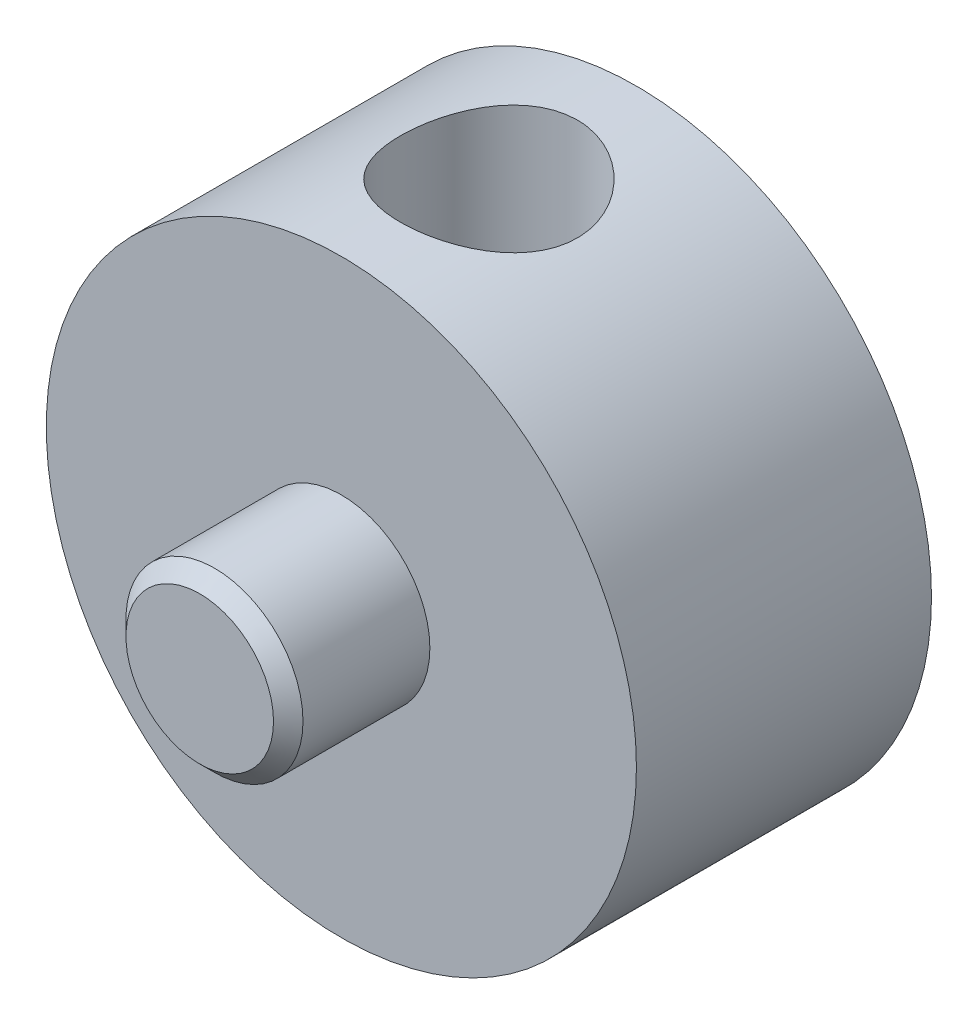
SolidWorks part; units mm, degrees
ref_plane "Piano frontale" through (0, 0, 0) normal (0, 0, 1) x (1, 0, 0)
ref_plane "Piano superiore" through (0, 0, 0) normal (0, 1, 0) x (1, 0, 0)
ref_plane "Piano destro" through (0, 0, 0) normal (1, 0, 0) x (0, 0, -1)
sketch "Schizzo1" plane through (0, 0, 0) normal (0, 0, 1) x (1, 0, 0)
  circle A0 centre (0, 0) radius 10
  dimension "D1" = 20
extrude "Estrusione-Estrusione1" add sketch "Schizzo1" along normal blind 10
ref_plane "Piano1" through (0, 0, 5) normal (0, 0, 1) x (1, 0, 0)
sketch "Schizzo2" plane through (0, 0, 5) normal (0, 0, 1) x (1, 0, 0)
  circle A0 centre (0, 0) radius 3
  dimension "D1" = 6
extrude "Estrusione-Estrusione2" add sketch "Schizzo2" along normal mid plane 19.6
chamfer "Smusso1" distance 0.5 angle 45 2 edges at (3, 0, 14.8) (3, 0, -4.8)
sketch "Schizzo3" plane through (0, 0, 0) normal (0, 1, 0) x (1, 0, 0)
  line L0 (0, 0) -> (0, -10) construction
  line L1 (-3, -10) -> (3, -10) construction
  line L2 (-10, -5) -> (10, -5) construction
  line L3 (-10, 0) -> (-10, -10) construction
  line L4 (10, -10) -> (10, 0) construction
  circle A0 centre (0, -5) radius 3
  dimension "D1" = 6
extrude "Taglio-Estrusione1" cut sketch "Schizzo3" along normal blind 9.5 from offset 0.5
